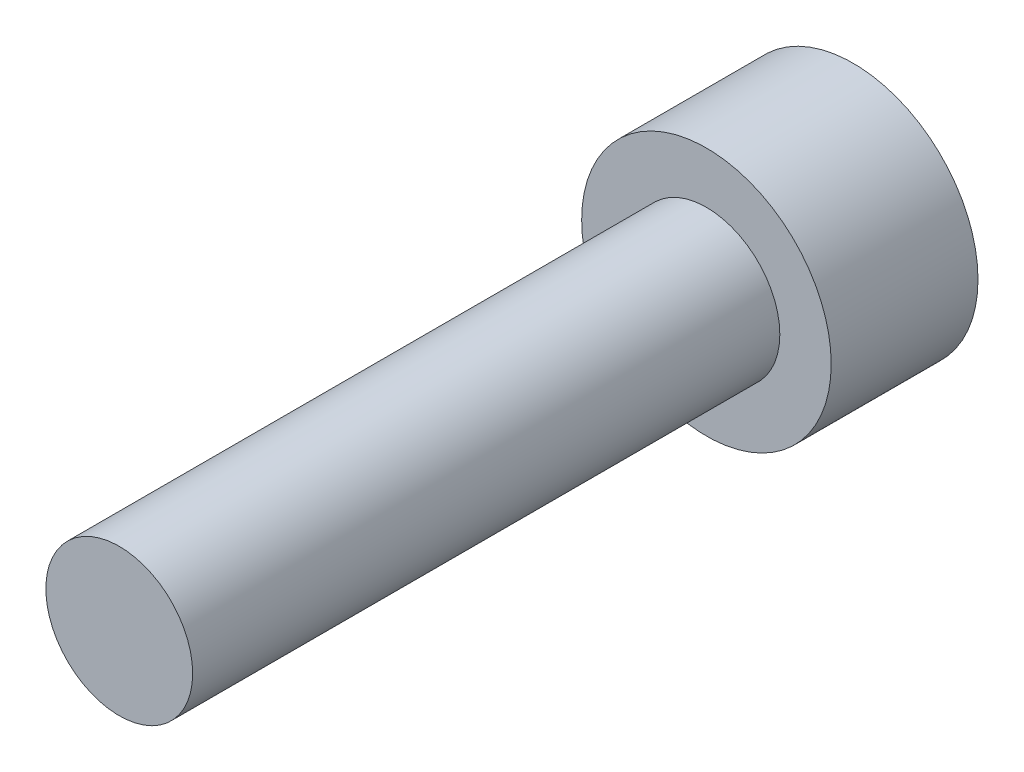
SolidWorks part; units mm, degrees
material "AISI 4340 Steel, normalized"
ref_plane "Front Plane" through (0, 0, 0) normal (0, 0, 1) x (1, 0, 0)
ref_plane "Top Plane" through (0, 0, 0) normal (0, 1, 0) x (1, 0, 0)
ref_plane "Right Plane" through (0, 0, 0) normal (1, 0, 0) x (0, 0, -1)
sketch "Sketch1" plane through (0, 0, 0) normal (0, 0, 1) x (1, 0, 0)
  circle A0 centre (0, 0) radius 4.25
extrude "Head_Envelope" add sketch "Sketch1" along normal blind 5 from offset 5
sketch "Sketch2" plane through (0, 0, 0) normal (0, 0, 1) x (1, 0, 0)
  circle A0 centre (0, 0) radius 2.5
extrude "Thread_Major_Envelope" add sketch "Sketch2" along normal blind 20
